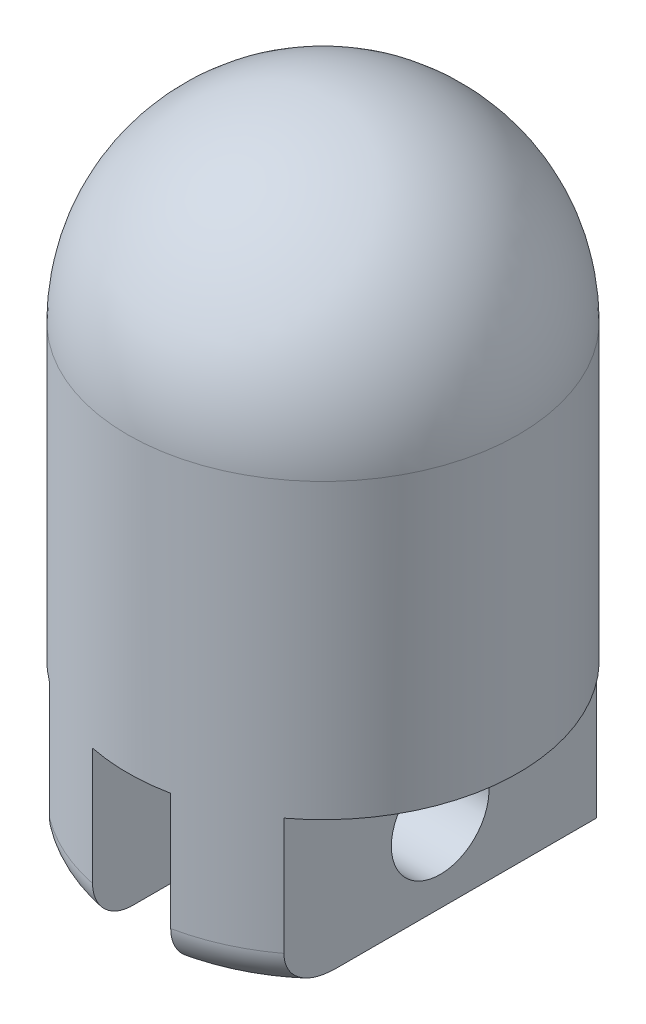
SolidWorks part; units mm, degrees
ref_plane "Front Plane" through (0, 0, 0) normal (0, 0, 1) x (1, 0, 0)
ref_plane "Top Plane" through (0, 0, 0) normal (0, 1, 0) x (1, 0, 0)
ref_plane "Right Plane" through (0, 0, 0) normal (1, 0, 0) x (0, 0, -1)
sketch "Sketch1" plane through (0, 0, 0) normal (0, 0, 1) x (1, 0, 0)
  line L0 (0, 0) -> (0, 5.6026)
  line L1 (0, 0) -> (-12.7, 0)
  line L2 (-12.7, 0) -> (-12.7, 29.21)
  line L6 (0, 5.6026) -> (-2.54, 5.6026)
  line L7 (-2.54, 22.86) -> (-2.54, 5.6026)
  line L8 (0, 36.0492) -> (0, 41.91)
  arc A0 (0, 41.91) -> (-12.7, 29.21) centre (0, 29.21) ccw
  arc A1 (-2.54, 22.86) -> (0, 36.0492) centre (0, 29.21) cw
  dimension "D3" = 25.4
  dimension "D1" = 41.91
  dimension "D2" = 12.7
  dimension "D4" = 2.54
revolve "Revolve1" add sketch "Sketch1" angle 360 about L0
sketch "Sketch2" plane through (0, 0, 0) normal (0, -1, 0) x (1, 0, 0)
  line L0 (-2.54, 12.4434) -> (-2.54, -12.4434)
  line L1 (-7.62, 10.16) -> (-7.62, -10.16)
  line L2 (2.54, 12.4434) -> (2.54, -12.4434)
  line L3 (7.62, 10.16) -> (7.62, -10.16)
  circle A0 centre (0, 0) radius 12.7 construction
  arc A1 (-7.62, 10.16) -> (-7.62, -10.16) centre (0, 0) ccw
  arc A2 (-2.54, -12.4434) -> (2.54, -12.4434) centre (0, 0) ccw
  arc A3 (7.62, -10.16) -> (7.62, 10.16) centre (0, 0) ccw
  arc A4 (2.54, 12.4434) -> (-2.54, 12.4434) centre (0, 0) ccw
  dimension "D1" = 2.54
  dimension "D2" = 5.08
  dimension "D3" = 2.54
  dimension "D4" = 5.08
extrude "Cut-Extrude1" cut sketch "Sketch2" against normal blind 10.16
sketch "Sketch3" plane through (-7.62, 0, 0) normal (-1, 0, 0) x (0, 0, 1)
  line L0 (0, -13.97) -> (0, 13.97) construction
  line L1 (-10.16, 0) -> (10.16, 0) construction
  circle A0 centre (0, 5.08) radius 3.175
  dimension "D2" = 6.35
  dimension "D1" = 5.08
extrude "Cut-Extrude2" cut sketch "Sketch3" against normal through all
fillet "Fillet1" radius 2.54 2 edges at (-5.2067, 0, 11.5836) (5.2067, 0, 11.5836)
